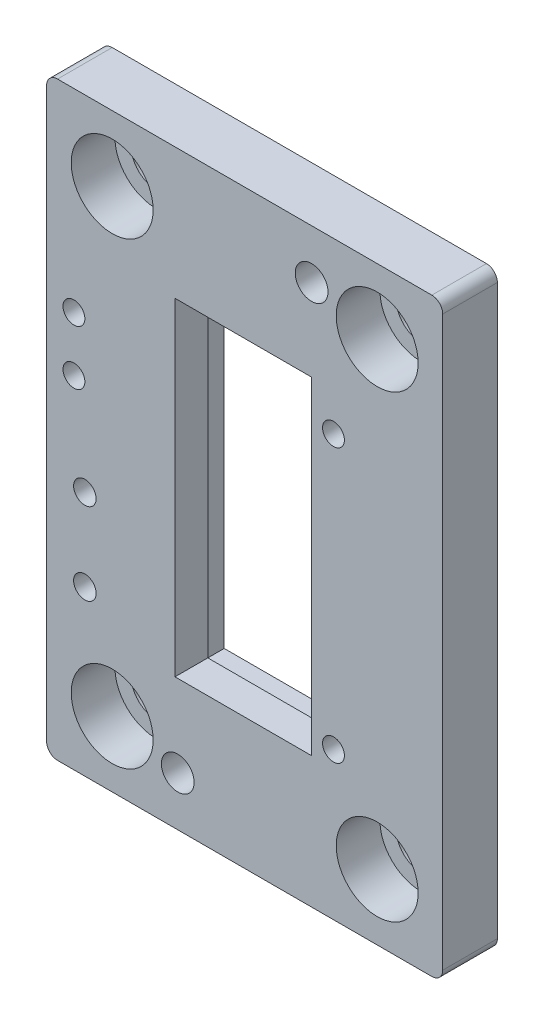
SolidWorks part; units mm, degrees
ref_plane "FP" through (0, 0, 0) normal (0, 0, 1) x (1, 0, 0)
ref_plane "TP" through (0, 0, 0) normal (0, 1, 0) x (1, 0, 0)
ref_plane "RP" through (0, 0, 0) normal (1, 0, 0) x (0, 0, -1)
sketch "Sketch1" plane through (0, 0, 0) normal (0, 0, 1) x (1, 0, 0)
  line L2 (22, 52) -> (22, -52)
  line L3 (24, -54) -> (36, -54)
  line L7 (24, 54) -> (92.5, 54)
  line L8 (94.5, 52) -> (94.5, -52)
  line L9 (92.5, -54) -> (36, -54)
  line L10 (70.5, -30) -> (70.5, 30) construction
  line L11 (45.5, -30) -> (45.5, 30) construction
  line L12 (45.5, 30) -> (70.5, 30) construction
  line L13 (45.5, -30) -> (70.5, -30) construction
  line L14 (45.5, -30) -> (70.5, -30)
  line L15 (45.5, -30) -> (45.5, 30)
  line L16 (45.5, 30) -> (70.5, 30)
  line L17 (70.5, -30) -> (70.5, 30)
  arc A0 (22, 52) -> (24, 54) centre (24, 52) cw
  arc A1 (22, -52) -> (24, -54) centre (24, -52) ccw
  arc A2 (94.5, -52) -> (92.5, -54) centre (92.5, -52) cw
  arc A3 (92.5, 54) -> (94.5, 52) centre (92.5, 52) cw
  circle A32 centre (29, -24) radius 2.06
  circle A33 centre (29, -9) radius 2.06
  point P13 (22, -54)
  dimension "D1" = 7
  dimension "D4" = 2
  dimension "D5" = 4.12
  dimension "D2" = 14
  dimension "D3" = 24
  dimension "D6" = 24
  dimension "D8" = 24
extrude "Boss-Extrude1" add sketch "Sketch1" against normal blind 10
sketch "Sketch2" plane through (0, 0, 0) normal (0, 0, 1) x (1, 0, 0)
  line L28 (44.5, 31) -> (44.5, -31)
  line L29 (71.5, 31) -> (44.5, 31)
  line L30 (71.5, -31) -> (71.5, 31)
  line L31 (44.5, -31) -> (71.5, -31)
  line L32 (44.5, 31) -> (44.5, -31)
  line L33 (71.5, 31) -> (44.5, 31)
  line L34 (71.5, -31) -> (71.5, 31)
  line L35 (44.5, -31) -> (71.5, -31)
  circle A12 centre (29, -9) radius 3.06
  circle A13 centre (29, -9) radius 3.06
  circle A15 centre (29, -24) radius 3.06
  circle A16 centre (29, -24) radius 3.06
  dimension "D1" = 1
  dimension "D2" = 1
  dimension "D3" = 1
extrude "Cut-Extrude1" cut sketch "Sketch2" against normal blind 4 from offset 6 offset against normal yes
sketch "Sketch3" plane through (0, 0, 0) normal (0, 0, 1) x (1, 0, 0)
  line L0 (25, 22) -> (25, 5) construction
  line L2 (25, 13.5) -> (52.8967, 13.5) construction
  line L3 (72.5, -32) -> (72.5, 32) construction
  line L4 (72.5, 0) -> (102.6103, 0) construction
  line L5 (43.5, -32) -> (72.5, -32) construction
  circle A0 centre (27, 8.5) radius 2
  circle A2 centre (27, 18.5) radius 2
  circle A3 centre (74.5, 23) radius 2
  circle A4 centre (74.5, -27) radius 2
  dimension "D1" = 4
  dimension "D3" = 4
  dimension "D2" = 10
  dimension "D4" = 5
  dimension "D5" = 50
extrude "Cut-Extrude2" cut sketch "Sketch3" against normal blind 7.5
hole_wizard "CBORE for M8 SHCS1" positions "Sketch4" profile "Sketch5" counterbore size "M8" standard "ANSI Metric" end condition through all
sketch "Sketch4" plane through (0, 0, 0) normal (0, 0, 1) x (0.9063, -0.4226, 0)
  point P0 (57.0204, 72.9309)
  point P1 (13.0645, 52.4339)
  point P2 (48.5644, -23.6959)
  point P3 (92.5204, -3.1989)
sketch "Sketch5" plane through (82.5, 42, 0) normal (1, 0, 0) x (0, -1, 0)
  line L0 (0, 0) -> (0, 10)
  line L1 (0, 10) -> (4.5, 10)
  line L2 (4.5, 10) -> (4.5, 8)
  line L3 (4.5, 8) -> (7.5, 8)
  line L4 (7.5, 8) -> (7.5, 0)
  line L5 (7.5, 0) -> (0, 0)
  line L6 (0, -6.35) -> (0, 107.95) construction
  dimension "Thru Hole Dia." = 9
  dimension "Thru Hole Depth" = 10
  dimension "C'Bore Dia." = 15
  dimension "C'Bore Depth" = 8
hole_wizard "Ø6.0mm Clearance Dowel Hole1" positions "Sketch6" profile "Sketch7" hole size "Ø6.0" standard "ANSI Metric" end condition through all
sketch "Sketch6" plane through (0, 0, 0) normal (0, 0, 1) x (0.9063, -0.4226, 0)
  point P0 (44.8769, 70.5784)
  point P1 (60.708, -21.3434)
sketch "Sketch7" plane through (70.5, 45, 0) normal (1, 0, 0) x (0, -1, 0)
  line L0 (0, 0) -> (0, 10)
  line L1 (0, 10) -> (3, 10)
  line L2 (3, 10) -> (3, 0)
  line L3 (3, 0) -> (0, 0)
  line L4 (0, -6.35) -> (0, 107.95) construction
  dimension "Thru Hole Dia." = 6
  dimension "Thru Hole Depth" = 10
